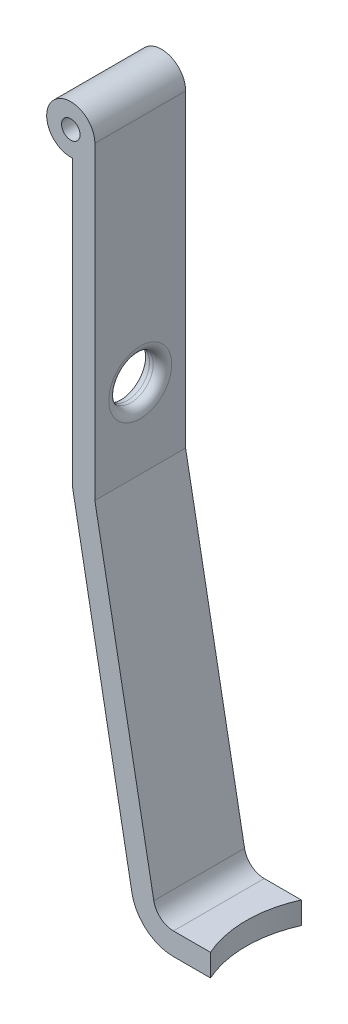
SolidWorks part; units mm, degrees
ref_plane "Front Plane" through (0, 0, 0) normal (0, 0, 1) x (1, 0, 0)
ref_plane "Top Plane" through (0, 0, 0) normal (0, 1, 0) x (1, 0, 0)
ref_plane "Right Plane" through (0, 0, 0) normal (1, 0, 0) x (0, 0, -1)
sketch "Sketch1" plane through (0, 0, 0) normal (0, 0, 1) x (1, 0, 0)
  line L0 (0.25, -3.2404) -> (0.25, -41.7404)
  line L2 (3.25, -41.7404) -> (3.25, 0)
  line L3 (13.8553, -86.7404) -> (18.8553, -86.7404)
  line L4 (18.8553, -86.7404) -> (18.8553, -89.7404)
  line L5 (18.8553, -89.7404) -> (13.8553, -89.7404)
  line L6 (0.25, -41.7404) -> (8.25, -85.0752)
  line L7 (3.25, -41.7404) -> (11.2007, -84.5336)
  circle A0 centre (0, 0) radius 1.25
  arc A1 (3.25, 0) -> (0.25, -3.2404) centre (0, 0) ccw
  arc A2 (8.25, -85.0752) -> (13.8553, -89.7404) centre (13.8553, -84.0404) ccw
  arc A3 (11.2007, -84.5336) -> (13.8553, -86.7404) centre (13.8553, -84.0404) ccw
  dimension "D1" = 2.5
  dimension "D2" = 2
  dimension "D5" = 5.4
  dimension "D7" = 3
  dimension "D3" = 3
  dimension "D4" = 45
  dimension "D6" = 5
  dimension "D9" = 38.5
  dimension "D10" = 8
extrude "Boss-Extrude1" add sketch "Sketch1" along normal blind 12.25
sketch "Sketch2" plane through (0.25, 0, 0) normal (-1, 0, 0) x (0, 0, 1)
  line L1 (6.125, 0) -> (6.125, -31) construction
  line L4 (6.125, 0) -> (17.3739, 0) construction
  line L5 (12.25, -41.7404) -> (0, -41.7404) construction
  circle A0 centre (6.125, -31) radius 3
  point P4 (6.125, -41.7404)
  dimension "D2" = 6
  dimension "D1" = 31
extrude "Cut-Extrude1" cut sketch "Sketch2" against normal up to next
fillet "Fillet1" radius 1.25 2 edges at (3.25, -34, 6.125) (0.25, -34, 6.125)
sketch "Sketch3" plane through (0.25, 0, 0) normal (-1, 0, 0) x (0, 0, 1)
  circle A0 centre (6.125, -31) radius 7.5
  circle A1 centre (6.125, -31) radius 3
  circle A2 centre (6.125, -31) radius 3 construction
  dimension "D1" = 15
extrude "Boss-Extrude2" [suppressed] add sketch "Sketch3" against normal up to surface (3 mm away)
sketch "Sketch4" plane through (0, -86.7404, 0) normal (0, 1, 0) x (1, 0, 0)
  line L0 (18.8553, 0) -> (18.8553, -12.25)
  arc A0 (18.8553, 0) -> (18.8553, -12.25) centre (32.5478, -6.125) ccw
  dimension "D1" = 15
extrude "Cut-Extrude2" cut sketch "Sketch4" against normal up to next
